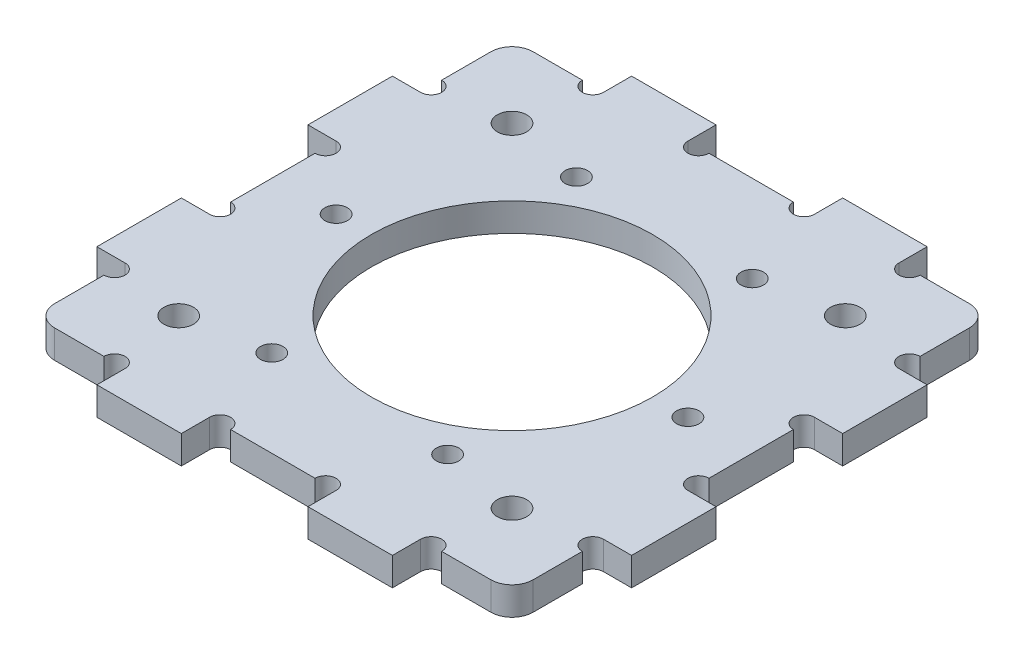
SolidWorks part; units mm, degrees
ref_plane "前视基准面" through (0, 0, 0) normal (0, 0, 1) x (1, 0, 0)
ref_plane "上视基准面" through (0, 0, 0) normal (0, 1, 0) x (1, 0, 0)
ref_plane "右视基准面" through (0, 0, 0) normal (1, 0, 0) x (0, 0, -1)
other "Configuration Table"
sketch "草图1" plane through (0, 0, 0) normal (0, 1, 0) x (1, 0, 0)
  line L1 (-34, -34) -> (34, -34)
  line L2 (-34, -34) -> (-34, 34)
  line L3 (-34, 34) -> (34, 34)
  line L4 (34, -34) -> (34, 34)
  line L5 (-34, -34) -> (34, 34) construction
  line L6 (-34, 34) -> (34, -34) construction
  circle A1 centre (0, 0) radius 20
  dimension "D1" = 68
  dimension "D2" = 40
  dimension "D3" = 68
extrude "凸台-拉伸1" add sketch "草图1" along normal blind 4
sketch "草图2" plane through (0, 4, 0) normal (0, 1, 0) x (1, 0, 0)
  line L0 (34, 34) -> (-34, 34) construction
  line L1 (-21, 34) -> (-9, 34)
  line L2 (-21, 34) -> (-21, 38)
  line L3 (-21, 38) -> (-9, 38)
  line L4 (-9, 34) -> (-9, 38)
  line L5 (0, 0) -> (0, 52.3077) construction
  line L6 (21, 34) -> (9, 34)
  line L7 (9, 34) -> (9, 38)
  line L8 (21, 38) -> (9, 38)
  line L9 (21, 34) -> (21, 38)
  line L10 (34, 21) -> (38, 21)
  line L11 (38, 21) -> (38, 9)
  line L12 (34, 21) -> (34, 9)
  line L13 (34, 9) -> (38, 9)
  line L14 (34, -9) -> (38, -9)
  line L15 (38, -21) -> (38, -9)
  line L16 (34, -21) -> (34, -9)
  line L17 (34, -21) -> (38, -21)
  line L18 (21, -34) -> (21, -38)
  line L19 (21, -38) -> (9, -38)
  line L20 (21, -34) -> (9, -34)
  line L21 (9, -34) -> (9, -38)
  line L22 (-9, -34) -> (-9, -38)
  line L23 (-21, -38) -> (-9, -38)
  line L24 (-21, -34) -> (-9, -34)
  line L25 (-21, -34) -> (-21, -38)
  line L26 (-34, -21) -> (-38, -21)
  line L27 (-38, -21) -> (-38, -9)
  line L28 (-34, -21) -> (-34, -9)
  line L29 (-34, -9) -> (-38, -9)
  line L30 (-34, 9) -> (-38, 9)
  line L31 (-38, 21) -> (-38, 9)
  line L32 (-34, 21) -> (-34, 9)
  line L33 (-34, 21) -> (-38, 21)
  dimension "D1" = 4
  dimension "D2" = 12
  dimension "D3" = 18
  dimension "D4" = 4
extrude "凸台-拉伸2" add sketch "草图2" against normal blind 4
sketch "草图3" plane through (0, 4, 0) normal (0, 1, 0) x (1, 0, 0)
  line L0 (-21, 34) -> (-34, 34) construction
  line L1 (9, 34) -> (-9, 34) construction
  line L2 (34, 21) -> (34, 34) construction
  line L3 (34, 34) -> (21, 34) construction
  line L4 (34, -9) -> (34, 9) construction
  line L5 (34, -34) -> (34, -21) construction
  line L6 (21, -34) -> (34, -34) construction
  line L7 (-9, -34) -> (9, -34) construction
  line L8 (-34, -34) -> (-21, -34) construction
  line L9 (-34, -21) -> (-34, -34) construction
  line L10 (-34, 9) -> (-34, -9) construction
  line L11 (-34, 34) -> (-34, 21) construction
  circle A0 centre (-22.5, 34) radius 1.5
  circle A1 centre (-7.5, 34) radius 1.5
  circle A2 centre (7.5, 34) radius 1.5
  circle A4 centre (22.5, 34) radius 1.5
  circle A5 centre (34, 22.5) radius 1.5
  circle A6 centre (34, 7.5) radius 1.5
  circle A7 centre (34, -7.5) radius 1.5
  circle A8 centre (34, -22.5) radius 1.5
  circle A9 centre (22.5, -34) radius 1.5
  circle A10 centre (7.5, -34) radius 1.5
  circle A11 centre (-7.5, -34) radius 1.5
  circle A12 centre (-22.5, -34) radius 1.5
  circle A13 centre (-34, -22.5) radius 1.5
  circle A14 centre (-34, -7.5) radius 1.5
  circle A15 centre (-34, 7.5) radius 1.5
  circle A16 centre (-34, 22.5) radius 1.5
  dimension "D1" = 3
extrude "切除-拉伸1" cut sketch "草图3" against normal blind 4
fillet "圆角1" radius 3 4 edges at (-34, 2, 34) (34, 2, 34) (34, 2, -34) (-34, 2, -34)
sketch "草图4" plane through (0, 4, 0) normal (0, 1, 0) x (1, 0, 0)
  circle A0 centre (0, 0) radius 25 construction
  circle A1 centre (25, 0) radius 1.6
  circle A2 centre (12.5, -21.6506) radius 1.6
  circle A3 centre (-12.5, -21.6506) radius 1.6
  circle A4 centre (-25, 0) radius 1.6
  circle A5 centre (-12.5, 21.6506) radius 1.6
  circle A6 centre (12.5, 21.6506) radius 1.6
  dimension "D1" = 50
  dimension "D2" = 3.2
  dimension "D3" = 6
extrude "切除-拉伸2" cut sketch "草图4" against normal blind 10
sketch "草图5" plane through (0, 4, 0) normal (0, 1, 0) x (1, 0, 0)
  line L0 (0, 0) -> (23.6881, 23.6881) construction
  line L1 (0, 0) -> (15.5967, 0) construction
  circle A0 centre (0, 0) radius 33.5 construction
  circle A1 centre (23.6881, 23.6881) radius 2.1
  circle A2 centre (23.6881, -23.6881) radius 2.1
  circle A3 centre (-23.6881, -23.6881) radius 2.1
  circle A4 centre (-23.6881, 23.6881) radius 2.1
  dimension "D1" = 67
  dimension "D3" = 4.2
  dimension "D2" = 45
  dimension "D4" = 4
extrude "切除-拉伸3" cut sketch "草图5" against normal blind 5
